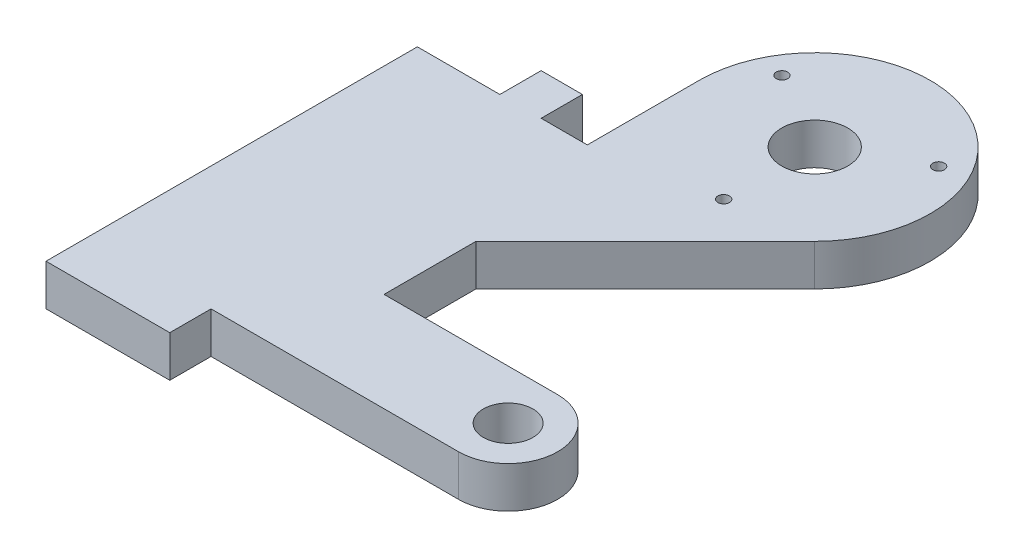
SolidWorks part; units mm, degrees
ref_plane "Front Plane" through (0, 0, 0) normal (0, 0, 1) x (1, 0, 0)
ref_plane "Top Plane" through (0, 0, 0) normal (0, 1, 0) x (1, 0, 0)
ref_plane "Right Plane" through (0, 0, 0) normal (1, 0, 0) x (0, 0, -1)
sketch "Sketch1" plane through (0, 0, 0) normal (0, 1, 0) x (1, 0, 0)
  line L1 (0, 0) -> (45, 0)
  line L2 (0, 0) -> (0, 12)
  line L3 (0, 12) -> (45, 12)
  line L5 (0, 0) -> (15, 0)
  line L6 (0, 0) -> (0, -5)
  line L7 (0, -5) -> (15, -5)
  line L8 (15, 0) -> (15, -5)
  line L9 (0, 12) -> (24, 12)
  line L10 (0, 12) -> (0, 55.0692)
  line L11 (0, 55.0692) -> (24, 55.0692)
  line L12 (24, 12) -> (24, 55.0692)
  circle A0 centre (45, 6) radius 3
  arc A1 (45, 0) -> (45, 12) centre (45, 6) ccw
  circle A6 centre (12, 53.0692) radius 0.7
  circle A7 centre (21.5263, 36.5692) radius 0.7
  circle A8 centre (2.4737, 36.5692) radius 0.7
  circle A11 centre (12, 42.0692) radius 2
  dimension "D4" = 45
  dimension "D3" = 6
  dimension "D11" = 1.4
  dimension "D1" = 5
  dimension "D2" = 15
  dimension "D5" = 6
  dimension "D13" = 3
sketch "Sketch2" plane through (0, 0, 0) normal (0, 1, 0) x (1, 0, 0)
  line L0 (20.5944, 53.5625) -> (20.5944, 40)
  line L1 (0, 0) -> (15, 0)
  line L2 (0, 0) -> (0, -5)
  line L3 (0, -5) -> (15, -5)
  line L4 (15, 0) -> (15, -5)
  line L5 (0, 0) -> (23.9647, 0)
  line L6 (0, 0) -> (0, 40)
  line L7 (0, 40) -> (23.9647, 40)
  line L8 (23.9647, 0) -> (23.9647, 40)
  line L9 (15, 40) -> (10, 40)
  line L10 (15, 40) -> (15, 45)
  line L11 (15, 45) -> (10, 45)
  line L12 (10, 40) -> (10, 45)
  line L17 (27.1777, 26.3469) -> (44.4939, 43.6631)
  line L18 (44.4939, 43.6631) -> (23.9647, 23.1339)
  line L19 (45, 12) -> (23.9647, 12)
  line L20 (45, 0) -> (23.9647, 0)
  circle A0 centre (45, 6) radius 39.6875 construction
  circle A1 centre (34.5944, 53.5625) radius 9 construction
  arc A2 (45, 0) -> (45, 12) centre (45, 6) ccw
  circle A3 centre (45, 6) radius 3
  circle A4 centre (34.5574, 42.5626) radius 0.7
  circle A8 centre (25.0866, 59.0945) radius 0.7
  circle A9 centre (44.1391, 59.0305) radius 0.7
  circle A10 centre (34.5944, 53.5625) radius 14
  circle A11 centre (34.5944, 53.5625) radius 4
  dimension "D5" = 79.375
  dimension "D6" = 18
  dimension "D7" = 11
  dimension "D8" = 3
  dimension "D9" = 45
  dimension "D1" = 40
  dimension "D2" = 5
  dimension "D3" = 5
  dimension "D4" = 0
extrude "Boss-Extrude2" add sketch "Sketch2" along normal blind 5
